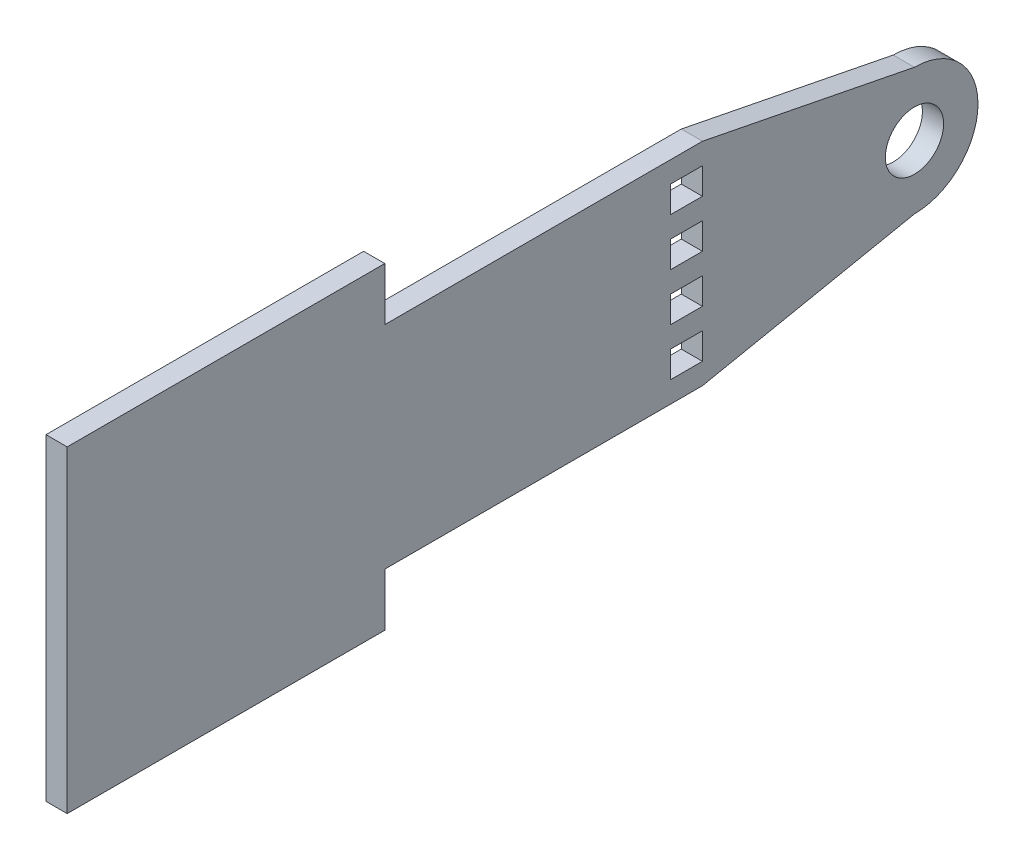
SolidWorks part; units mm, degrees
ref_plane "Front Plane" through (0, 0, 0) normal (0, 0, 1) x (1, 0, 0)
ref_plane "Top Plane" through (0, 0, 0) normal (0, 1, 0) x (1, 0, 0)
ref_plane "Right Plane" through (0, 0, 0) normal (1, 0, 0) x (0, 0, -1)
sketch "Sketch1" plane through (0, 0, 0) normal (1, 0, 0) x (0, 0, -1)
  line L0 (30, 10) -> (0, 10)
  line L1 (0, 10) -> (0, 15)
  line L2 (0, 15) -> (-30, 15)
  line L3 (-30, 15) -> (-30, -15)
  line L4 (-30, -15) -> (0, -15)
  line L5 (0, -15) -> (0, -10)
  line L6 (0, -10) -> (30, -10)
  line L7 (30, -5.5) -> (30, -8)
  line L8 (30, -8) -> (27, -8)
  line L9 (27, -8) -> (27, -5.5)
  line L10 (27, -5.5) -> (30, -5.5)
  line L11 (50.0283, 6.0416) -> (30, 10)
  line L12 (30, -3.5) -> (27, -3.5)
  line L13 (27, -3.5) -> (27, -1)
  line L14 (27, -1) -> (30, -1)
  line L15 (50.0283, -5.9584) -> (30, -10)
  line L16 (30, 1) -> (27, 1)
  line L17 (27, 1) -> (27, 3.5)
  line L18 (27, 3.5) -> (30, 3.5)
  line L20 (30, 5.5) -> (27, 5.5)
  line L21 (27, 5.5) -> (27, 8)
  line L22 (27, 8) -> (30, 8)
  line L26 (50.0283, 0.0416) -> (30.0283, 0.0416) construction
  line L27 (30, 8) -> (30, 5.5)
  line L28 (30, 3.5) -> (30, 1)
  line L29 (30, -1) -> (30, -3.5)
  circle A0 centre (50.0283, 0.0416) radius 2.75
  arc A1 (50.0283, -5.9584) -> (50.0283, 6.0416) centre (50.0283, 0.0416) ccw
  point P9 (30, 0)
  point P25 (-30, 0)
  point P30 (50.0283, 0.0416)
  dimension "D7" = 5.5
  dimension "D8" = 12
  dimension "D13" = 5.5
  dimension "D1" = 2
  dimension "D2" = 2.5
  dimension "D3" = 30
  dimension "D4" = 30
  dimension "D5" = 30
  dimension "D6" = 3
  dimension "D9" = 1
  dimension "D10" = 5.5
  dimension "D11" = 1
  dimension "D12" = 5.5
  dimension "D14" = 50.0283
extrude "Boss-Extrude1" add sketch "Sketch1" along normal blind 2
